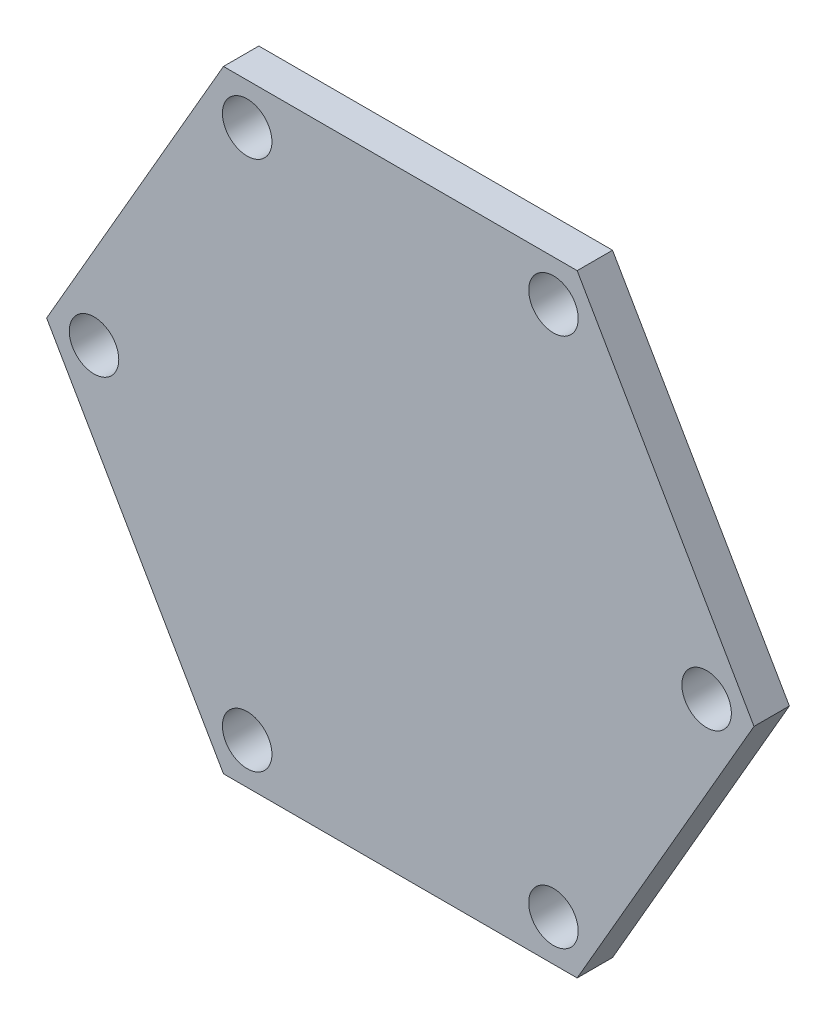
SolidWorks part; units mm, degrees
ref_plane "Płaszczyzna przednia" through (0, 0, 0) normal (0, 0, 1) x (1, 0, 0)
ref_plane "Płaszczyzna górna" through (0, 0, 0) normal (0, 1, 0) x (1, 0, 0)
ref_plane "Płaszczyzna prawa" through (0, 0, 0) normal (1, 0, 0) x (0, 0, -1)
sketch "Szkic1" plane through (0, 0, 0) normal (0, 0, 1) x (1, 0, 0)
  line L1 (50, 86.6025) -> (-50, 86.6025)
  line L2 (-50, 86.6025) -> (-100, 0)
  line L3 (-100, 0) -> (-50, -86.6025)
  line L4 (-50, -86.6025) -> (50, -86.6025)
  line L5 (50, -86.6025) -> (100, 0)
  line L6 (100, 0) -> (50, 86.6025)
  circle A0 centre (0, 0) radius 86.6025 construction
  circle A1 centre (-43.3013, 75) radius 7
  circle A2 centre (43.3013, 75) radius 7
  circle A3 centre (86.6025, 0) radius 7
  circle A4 centre (43.3013, -75) radius 7
  circle A5 centre (-43.3013, -75) radius 7
  circle A6 centre (-86.6025, 0) radius 7
  point P23 (0, 0)
  dimension "D2" = 14
  dimension "D1" = 100
  dimension "D3" = 6
extrude "Dodanie-wyciągnięcie1" add sketch "Szkic1" along normal blind 10
